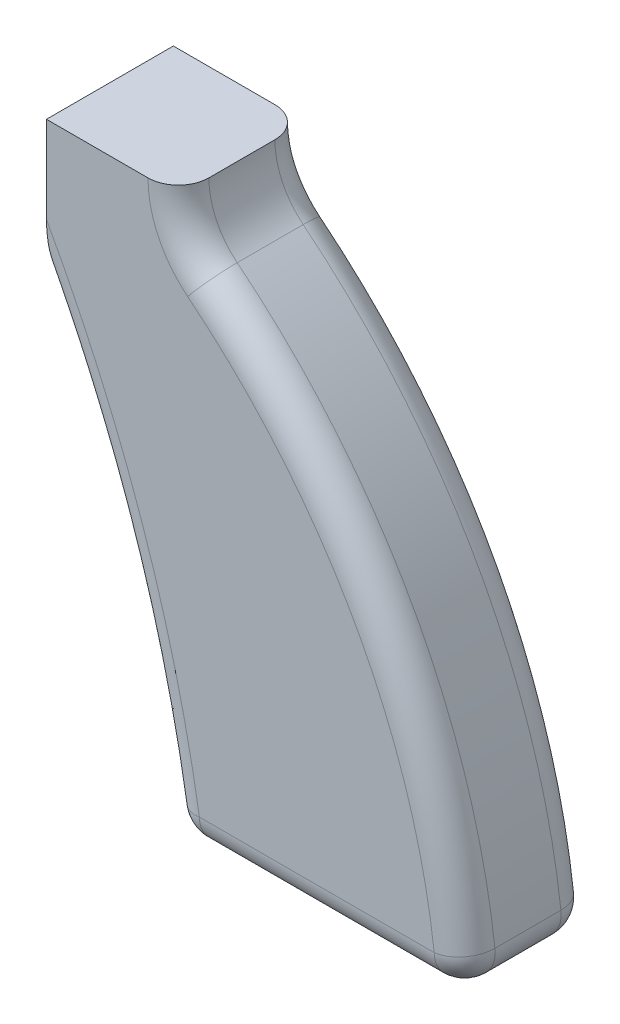
SolidWorks part; units mm, degrees
ref_plane "前视基准面" through (0, 0, 0) normal (0, 0, 1) x (1, 0, 0)
ref_plane "上视基准面" through (0, 0, 0) normal (0, 1, 0) x (1, 0, 0)
ref_plane "右视基准面" through (0, 0, 0) normal (1, 0, 0) x (0, 0, -1)
other "Configuration Table"
sketch "草图1" plane through (0, 0, 0) normal (0, 0, 1) x (1, 0, 0)
  line L0 (0, 0) -> (26, 0)
  line L2 (0, 0) -> (0, -30)
  line L5 (83, -110) -> (25, -110)
  arc A3 (31.5863, -11.6783) -> (83, -110) centre (-55.6472, -119.8971) cw
  arc A4 (0, -30) -> (25, -110) centre (-237.2543, -148.0482) cw
  arc A6 (26, 0) -> (31.5863, -11.6783) centre (41, 0) ccw
  dimension "D3" = 15
  dimension "D6" = 58
  dimension "D7" = 25
  dimension "D4" = 139
  dimension "D5" = 265
  dimension "D8" = 110
  dimension "D1" = 26
  dimension "D2" = 30
extrude "凸台-拉伸1" add sketch "草图1" along normal mid plane 25
fillet "圆角1" radius 6 10 edges at (27.4685, -6.4728, -12.5) (27.4685, -6.4728, 12.5) (25, -110, 0) (54, -110, -12.5) (54, -110, 12.5) (83, -110, 0) (15.6829, -69.0054, -12.5) (15.6829, -69.0054, 12.5) (67.5287, -55.4868, -12.5) (67.5287, -55.4868, 12.5)
